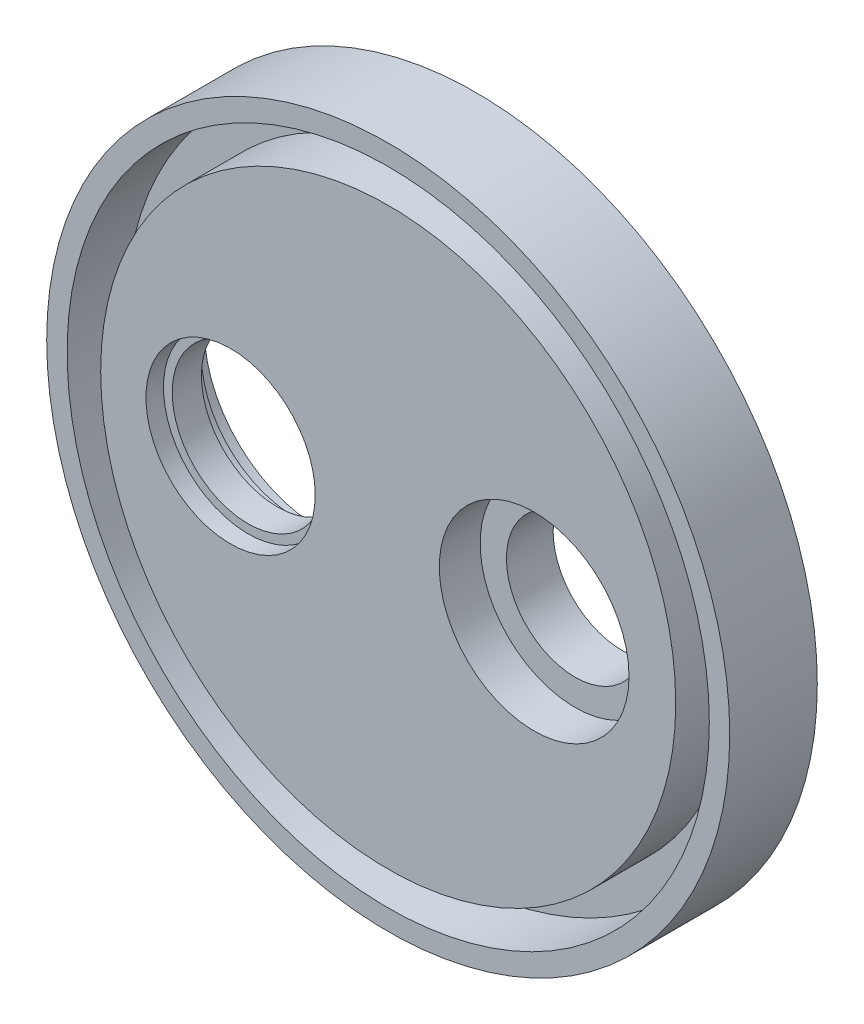
SolidWorks part; units mm, degrees
ref_plane "Ön Düzlem" through (0, 0, 0) normal (0, 0, 1) x (1, 0, 0)
ref_plane "Üst Düzlem" through (0, 0, 0) normal (0, 1, 0) x (1, 0, 0)
ref_plane "Sağ Düzlem" through (0, 0, 0) normal (1, 0, 0) x (0, 0, -1)
sketch "Sketch1" plane through (0, 0, 0) normal (0, 0, 1) x (1, 0, 0)
  circle A0 centre (0, 0) radius 58.5
  dimension "D1" = 117
extrude "Boss-Extrude1" add sketch "Sketch1" along normal blind 15
sketch "Sketch2" plane through (0, 0, 15) normal (0, 0, 1) x (1, 0, 0)
  circle A0 centre (0, 0) radius 55
  circle A1 centre (0, 0) radius 49.25
  dimension "D1" = 110
  dimension "D2" = 98.5
extrude "Cut-Extrude1" cut sketch "Sketch2" against normal blind 10
sketch "Sketch3" plane through (0, 0, 0) normal (0, 0, -1) x (-1, 0, 0)
  circle A0 centre (-25, 0) radius 11.75
  dimension "D1" = 23.5
  dimension "D2" = 25
extrude "Cut-Extrude2" cut sketch "Sketch3" against normal through all
sketch "Sketch4" plane through (0, 0, 15) normal (0, 0, 1) x (1, 0, 0)
  circle A0 centre (25, 0) radius 16.25
  dimension "D1" = 32.5
extrude "Cut-Extrude3" cut sketch "Sketch4" against normal blind 7
sketch "Sketch5" plane through (0, 0, 0) normal (0, 0, -1) x (-1, 0, 0)
  circle A0 centre (27, 0) radius 19.5
  dimension "D1" = 39
  dimension "D2" = 27
extrude "Cut-Extrude4" cut sketch "Sketch5" against normal blind 4
sketch "Sketch6" plane through (0, 0, 4) normal (0, 0, -1) x (-1, 0, 0)
  circle A0 centre (27, 0) radius 16
  dimension "D1" = 32
extrude "Cut-Extrude5" cut sketch "Sketch6" against normal blind 3
sketch "Sketch7" plane through (0, 0, 15) normal (0, 0, 1) x (1, 0, 0)
  circle A0 centre (-27, 0) radius 14.5
  dimension "D1" = 29
  dimension "D2" = 27
extrude "Cut-Extrude6" cut sketch "Sketch7" against normal blind 3
sketch "Sketch8" plane through (0, 0, 12) normal (0, 0, 1) x (1, 0, 0)
  circle A0 centre (-27, 0) radius 13
  dimension "D1" = 26
extrude "Cut-Extrude7" cut sketch "Sketch8" against normal through all
